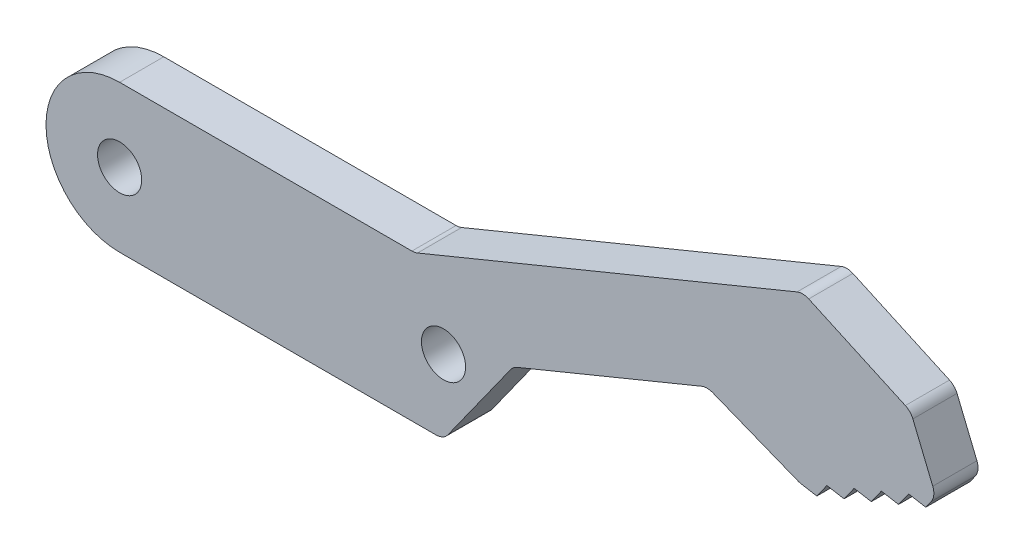
SolidWorks part; units mm, degrees
ref_plane "Front Plane" through (0, 0, 0) normal (0, 0, 1) x (1, 0, 0)
ref_plane "Top Plane" through (0, 0, 0) normal (0, 1, 0) x (1, 0, 0)
ref_plane "Right Plane" through (0, 0, 0) normal (1, 0, 0) x (0, 0, -1)
sketch "Sketch1" plane through (0, 0, 0) normal (0, 0, 1) x (1, 0, 0)
  line L0 (0, 0) -> (22, 0) construction
  line L1 (0, 5) -> (22, 5)
  line L2 (0, -5) -> (22, -5)
  line L3 (20.05, 5) -> (23.9914, -4.5863) construction
  line L4 (20.05, 5) -> (51.4959, 17.929) construction
  line L5 (23.9914, -4.5863) -> (55.4373, 8.3426) construction
  line L6 (51.4959, 17.929) -> (55.4373, 8.3426) construction
  line L7 (20.05, 5) -> (46.409, 15.8375)
  line L8 (46.409, 15.8375) -> (53.7261, 12.5046)
  line L9 (53.7261, 12.5046) -> (55.4373, 8.3426)
  line L10 (55.4373, 8.3426) -> (46.1885, 4.54) construction
  line L11 (46.1885, 4.54) -> (39.9002, 7.0361)
  line L12 (39.9002, 7.0361) -> (26.7299, 1.6211)
  line L13 (46.1885, 4.54) -> (47.3529, 4.3376)
  line L14 (47.3529, 4.3376) -> (48.0382, 5.3005)
  line L15 (47.3529, 4.3376) -> (54.752, 7.3797) construction
  line L16 (48.0382, 5.3005) -> (49.2027, 5.0981)
  line L17 (49.2027, 5.0981) -> (49.888, 6.0611)
  line L18 (49.888, 6.0611) -> (51.0524, 5.8587)
  line L19 (51.0524, 5.8587) -> (51.7378, 6.8216)
  line L20 (51.7378, 6.8216) -> (52.9022, 6.6192)
  line L21 (52.9022, 6.6192) -> (53.5875, 7.5821)
  line L22 (53.5875, 7.5821) -> (54.752, 7.3797)
  line L23 (54.752, 7.3797) -> (55.4373, 8.3426)
  line L24 (26.7299, 1.6211) -> (22, -5)
  arc A0 (0, 5) -> (0, -5) centre (0, 0) ccw
  arc A1 (22, -5) -> (22, 5) centre (22, 0) ccw
  circle A2 centre (0, 0) radius 1.5
  circle A3 centre (22, 0) radius 1.5
  point P3 (11, 0)
  dimension "D11" = 3
  dimension "D12" = 3
  dimension "D13" = 2
  dimension "D1" = 10
  dimension "D2" = 22
  dimension "D3" = 157.65
  dimension "D4" = 1.95
  dimension "D5" = 34
  dimension "D6" = 14.24
  dimension "D7" = 10
  dimension "D8" = 4.5
  dimension "D9" = 136
  dimension "D10" = 5.5
  dimension "D14" = 0.63
  dimension "D15" = 8
extrude "Boss-Extrude1" add sketch "Sketch1" along normal blind 3 contours A1 L1 A0 L2 A3 A2 | A1 L12 L11 L13 L14 L16 L17 L18 L19 L20 L21 L22 L23 L9 L8 L7 L1
fillet "Fillet1" radius 1 8 edges at (46.1885, 4.54, 1.5) (55.4373, 8.3426, 1.5) (53.7261, 12.5046, 1.5) (46.409, 15.8375, 1.5) (20.05, 5, 1.5) (39.9002, 7.0361, 1.5) (26.7299, 1.6211, 1.5) (22, -5, 1.5)
